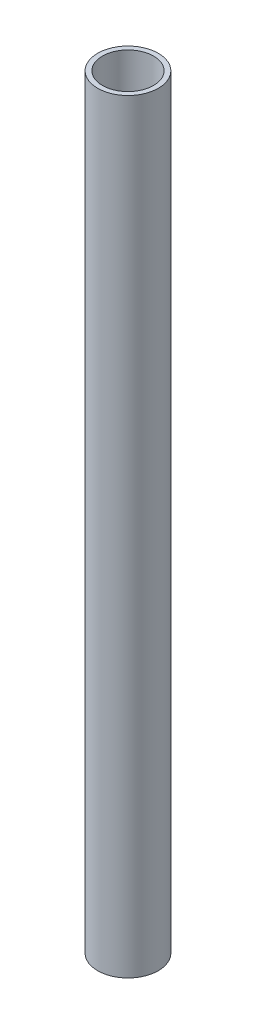
SolidWorks part; units mm, degrees
ref_plane "Front Plane" through (0, 0, 0) normal (0, 0, 1) x (1, 0, 0)
ref_plane "Top Plane" through (0, 0, 0) normal (0, 1, 0) x (1, 0, 0)
ref_plane "Right Plane" through (0, 0, 0) normal (1, 0, 0) x (0, 0, -1)
sketch "Sketch1" plane through (0, 0, 0) normal (0, 1, 0) x (1, 0, 0)
  circle A0 centre (0, 0) radius 12.7
  circle A1 centre (0, 0) radius 10.7
extrude "Boss-Extrude1" add sketch "Sketch1" along normal blind 320
